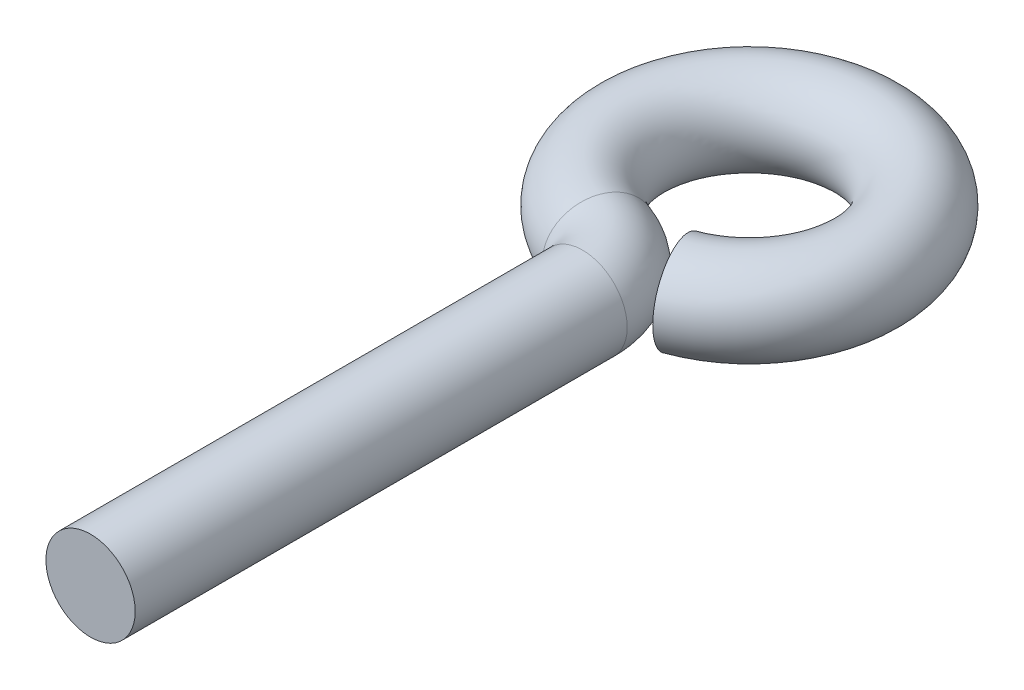
SolidWorks part; units mm, degrees
ref_plane "Front Plane" through (0, 0, 0) normal (0, 0, 1) x (1, 0, 0)
ref_plane "Top Plane" through (0, 0, 0) normal (0, 1, 0) x (1, 0, 0)
ref_plane "Right Plane" through (0, 0, 0) normal (1, 0, 0) x (0, 0, -1)
sketch "Sketch1" plane through (0, 0, 0) normal (0, 1, 0) x (1, 0, 0)
  line L0 (0, 0) -> (0, -43.884) construction
  line L1 (0, -6.9118) -> (0, -27.3)
  line L2 (0, 6.7) -> (0, 3) construction
  line L3 (1.6588, -4.5575) -> (0, 0) construction
  line L4 (6.2954, -4.85) -> (-6.2954, -4.85) construction
  circle A0 centre (0, 0) radius 4.85 construction
  arc A1 (1.6588, -4.5575) -> (-1.6497, -4.5608) centre (0, 0) ccw
  arc A2 (-1.6497, -4.5608) -> (0, -6.9118) centre (-2.5, -6.9118) cw
  point P12 (0, 4.85)
  point P15 (0, -4.85)
  dimension "D1" = 9.7
  dimension "D4" = 2.5
  dimension "D2" = 3.7
  dimension "D3" = 34
  dimension "D5" = 20
ref_plane "Plane1" through (0, 0, 27.3) normal (0, 0, 1) x (1, 0, 0)
sketch "Sketch2" plane through (0, 0, 27.3) normal (0, 0, 1) x (1, 0, 0)
  circle A0 centre (0, 0) radius 1.85
  dimension "D1" = 3.7
sweep "Sweep1" add profiles "Sketch2" path "Sketch1"
